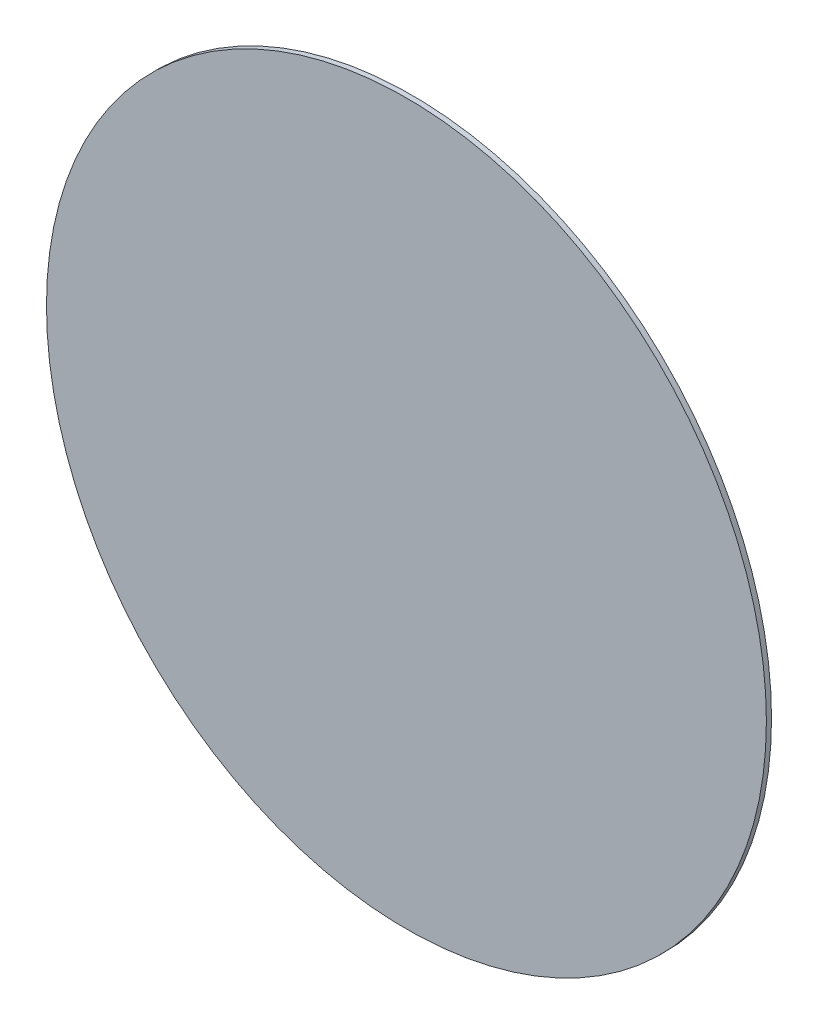
SolidWorks part; units mm, degrees
ref_plane "Front Plane" through (0, 0, 0) normal (1, 0, 0) x (0, 1, 0)
ref_plane "Top Plane" through (0, 0, 0) normal (0, 0, 1) x (0, 1, 0)
ref_plane "Right Plane" through (0, 0, 0) normal (0, 1, 0) x (-1, 0, 0)
sketch "Sketch1" plane through (0, 0, 0) normal (0, 0, 1) x (0, 1, 0)
  circle A0 centre (0, 0) radius 177.8
  dimension "D1" = 355.6
extrude "Boss-Extrude1" add sketch "Sketch1" along normal blind 2.54
